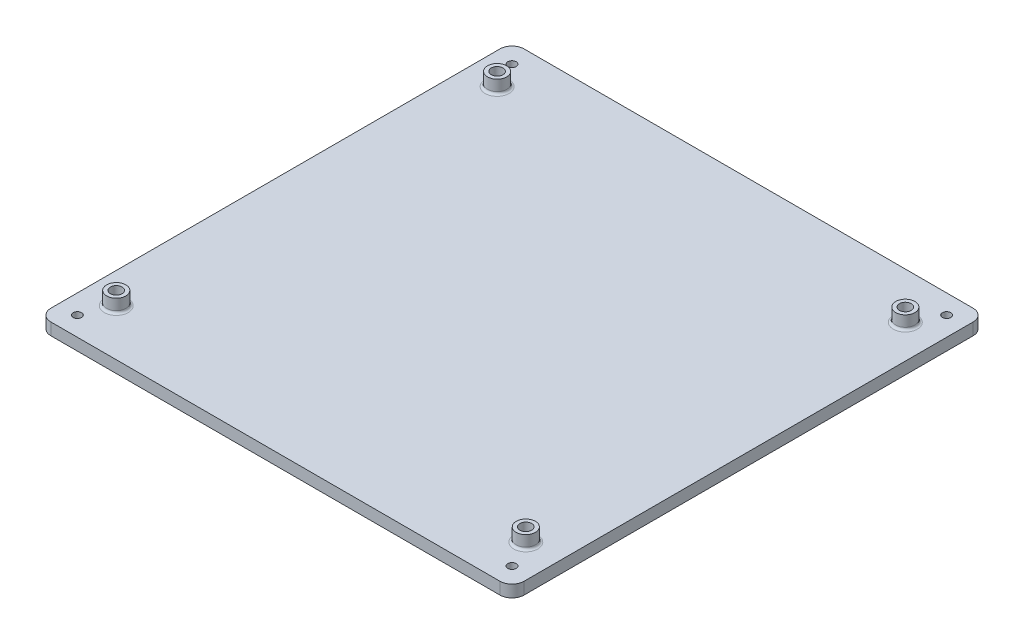
SolidWorks part; units mm, degrees
ref_plane "Front Plane" through (0, 0, 0) normal (0, 0, 1) x (1, 0, 0)
ref_plane "Top Plane" through (0, 0, 0) normal (0, 1, 0) x (1, 0, 0)
ref_plane "Right Plane" through (0, 0, 0) normal (1, 0, 0) x (0, 0, -1)
sketch "Sketch1" plane through (0, 0, 0) normal (0, 1, 0) x (1, 0, 0)
  line L0 (0, 0) -> (146.4799, 0) construction
  line L1 (0, 0) -> (0, 109.366) construction
  line L3 (-98.5, 98.5) -> (98.5, 98.5)
  line L4 (-98.5, 98.5) -> (-98.5, -98.5)
  line L5 (-98.5, -98.5) -> (98.5, -98.5)
  line L6 (98.5, 98.5) -> (98.5, -98.5)
  dimension "D1" = 197
  dimension "D2" = 197
  dimension "D3" = 98.5
  dimension "D4" = 98.5
extrude "Boss-Extrude1" add sketch "Sketch1" along normal blind 5
sketch "Sketch2" plane through (0, 0, 0) normal (0, 1, 0) x (1, 0, 0)
  line L0 (0, 0) -> (98.5, 0) construction
  line L1 (98.5, -98.5) -> (98.5, 98.5) construction
  line L2 (0, 0) -> (0, 98.5) construction
  line L3 (98.5, 98.5) -> (-98.5, 98.5) construction
  line L4 (-98.5, 98.5) -> (-98.5, -98.5) construction
  circle A0 centre (-90.5, 90.5) radius 1.75
  circle A1 centre (90.5, 90.5) radius 1.75
  circle A2 centre (90.5, -90.5) radius 1.75
  circle A3 centre (-90.5, -90.5) radius 1.75
  dimension "D4" = 3.5
  dimension "D1" = 8
  dimension "D2" = 8
extrude "Cut-Extrude1" cut sketch "Sketch2" along normal blind 5
fillet "Fillet1" radius 5 4 edges at (-98.5, 2.5, 98.5) (98.5, 2.5, 98.5) (98.5, 2.5, -98.5) (-98.5, 2.5, -98.5)
ref_plane "Plane2" through (0, 5, 0) normal (0, 1, 0) x (1, 0, 0)
sketch "Sketch5" plane through (0, 5, 0) normal (0, 1, 0) x (1, 0, 0)
  line L0 (0, 0) -> (0, 73.8278) construction
  line L1 (-89.5, 83) -> (89.5, 83) construction
  line L2 (-89.5, 83) -> (-89.5, -83) construction
  line L3 (-89.5, -83) -> (89.5, -83) construction
  line L4 (89.5, 83) -> (89.5, -83) construction
  line L5 (0, 0) -> (55.1078, 0) construction
  circle A0 centre (84.5, 79.3) radius 1.5 construction
  circle A1 centre (84.5, 79.3) radius 2.45
  circle A2 centre (84.5, 79.3) radius 4
  circle A3 centre (84.75, -79) radius 1.5 construction
  circle A4 centre (84.75, -79) radius 2.45
  circle A5 centre (84.75, -79) radius 4
  circle A6 centre (-85.8, -79) radius 1.5 construction
  circle A7 centre (-85.8, -79) radius 2.45
  circle A8 centre (-85.8, -79) radius 4
  circle A9 centre (-85.5, 79.3) radius 1.5 construction
  circle A10 centre (-85.5, 79.3) radius 2.45
  circle A11 centre (-85.5, 79.3) radius 4
  point P10 (86, 79.3)
  point P11 (84.5, 80.8)
  point P16 (86.25, -79)
  point P17 (84.75, -80.5)
  point P22 (-87.3, -79)
  point P23 (-85.8, -80.5)
  point P28 (-87, 79.3)
  point P29 (-85.5, 80.8)
  dimension "D5" = 3
  dimension "D8" = 4.9
  dimension "D9" = 8
  dimension "D10" = 3
  dimension "D13" = 4.9
  dimension "D14" = 8
  dimension "D15" = 3
  dimension "D18" = 4.9
  dimension "D19" = 8
  dimension "D20" = 3
  dimension "D23" = 4.9
  dimension "D24" = 8
  dimension "D1" = 179
  dimension "D2" = 166
  dimension "D3" = 89.5
  dimension "D4" = 83
  dimension "D6" = 3.5
  dimension "D7" = 2.2
  dimension "D11" = 3.25
  dimension "D12" = 2.5
  dimension "D16" = 2.2
  dimension "D17" = 2.5
  dimension "D21" = 2.2
  dimension "D22" = 2.5
extrude "Boss-Extrude2" add sketch "Sketch5" along normal blind 5.5
fillet "Fillet2" radius 1 4 edges at (84.75, 5, 83) (-85.8, 5, 83) (84.5, 5, -75.3) (-85.5, 5, -75.3)
sketch "Sketch6" plane through (0, 0, 0) normal (0, 1, 0) x (1, 0, 0)
  text T0 "<b>POLMAN X GEOLABX</b>\r\n" font "Century Gothic" height 10
extrude "Cut-Extrude2" cut sketch "Sketch6" along normal blind 3
sketch "Sketch7" plane through (0, 0, 0) normal (0, 1, 0) x (1, 0, 0)
  text T0 "<b>2022</b>" font "Century Gothic" height 10
extrude "Cut-Extrude4" cut sketch "Sketch7" along normal blind 3
